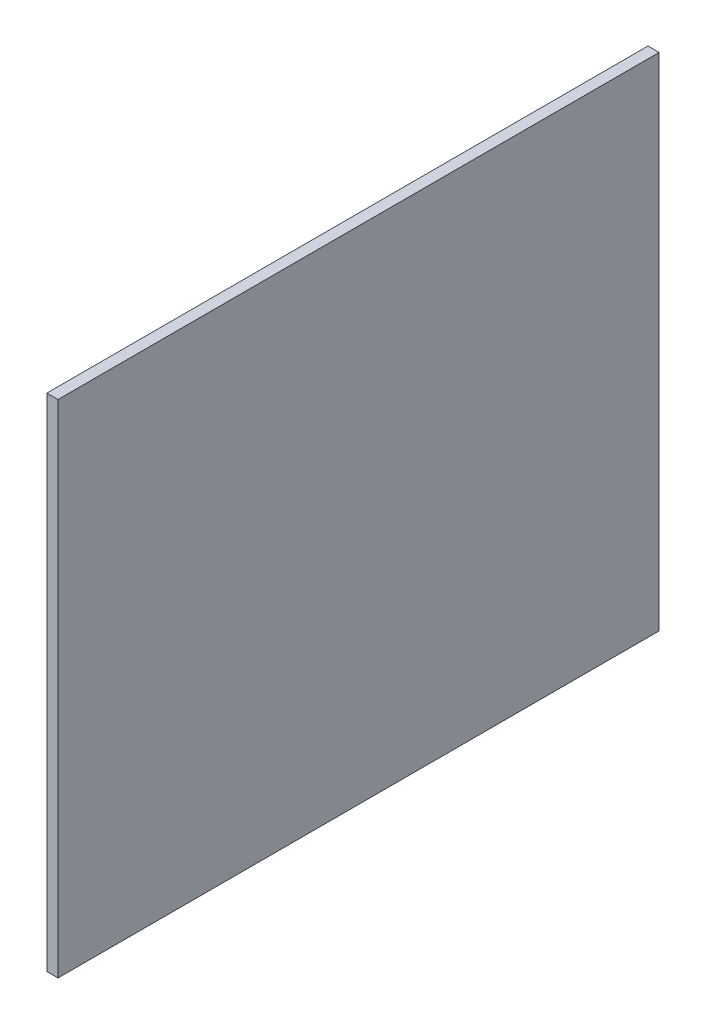
SolidWorks part; units mm, degrees
ref_plane "Front Plane" through (0, 0, 0) normal (0, 0, 1) x (1, 0, 0)
ref_plane "Top Plane" through (0, 0, 0) normal (0, 1, 0) x (1, 0, 0)
ref_plane "Right Plane" through (0, 0, 0) normal (1, 0, 0) x (0, 0, -1)
sketch "Sketch1" plane through (0, 0, 0) normal (1, 0, 0) x (0, 0, -1)
  line L1 (0, 0) -> (432, 0)
  line L2 (0, 0) -> (0, 360)
  line L3 (0, 360) -> (432, 360)
  line L4 (432, 0) -> (432, 360)
  dimension "D1" = 432
  dimension "D2" = 360
extrude "Boss-Extrude1" add sketch "Sketch1" along normal blind 8
